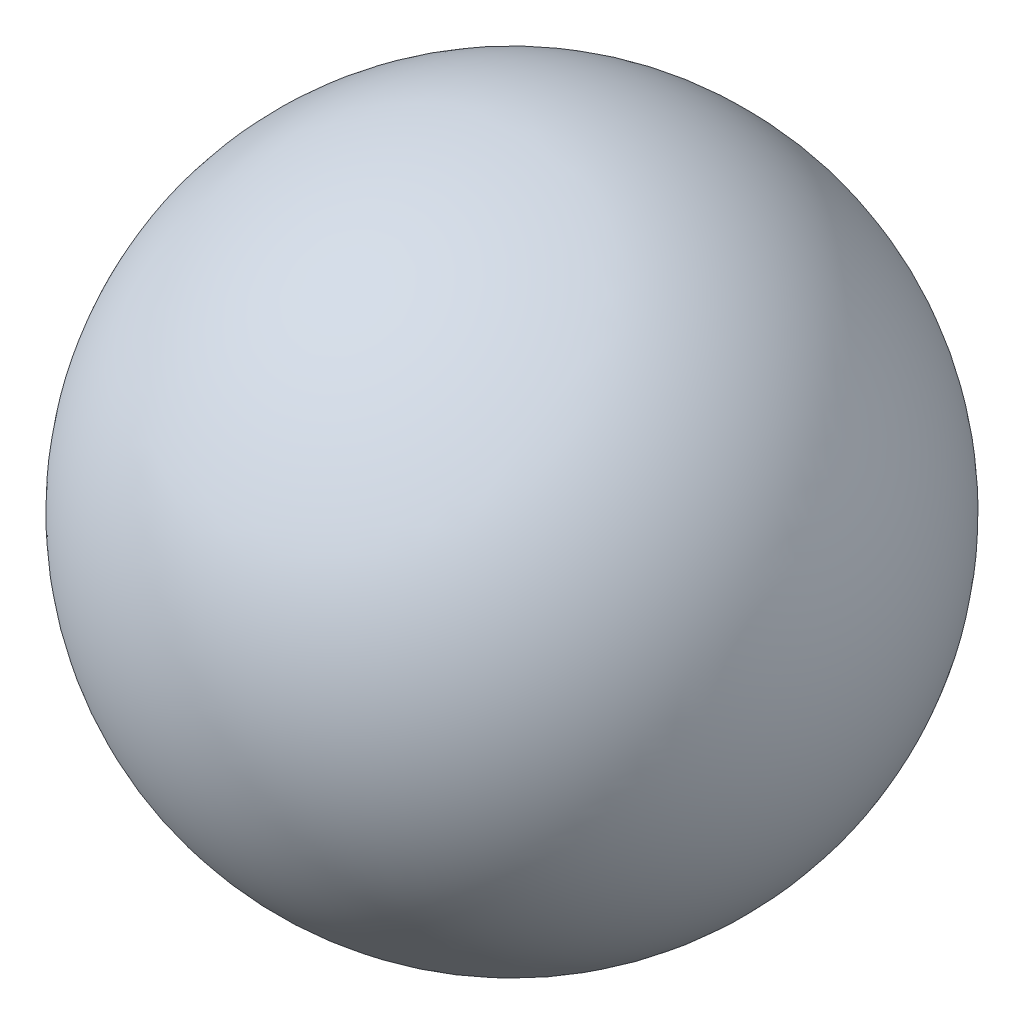
SolidWorks part; units mm, degrees
ref_plane "Front Plane" through (0, 0, 0) normal (0, 0, 1) x (1, 0, 0)
ref_plane "Top Plane" through (0, 0, 0) normal (0, 1, 0) x (1, 0, 0)
ref_plane "Right Plane" through (0, 0, 0) normal (1, 0, 0) x (0, 0, -1)
sketch "Sketch1" plane through (0, 0, 0) normal (0, 0, 1) x (1, 0, 0)
  line L0 (-25.4, 0) -> (25.4, 0)
  arc A0 (-25.4, 0) -> (25.4, 0) centre (0, 0) cw
  dimension "D1" = 25.4
  dimension "D2" = 50.8
revolve "Revolve1" add sketch "Sketch1" angle 360 about L0
